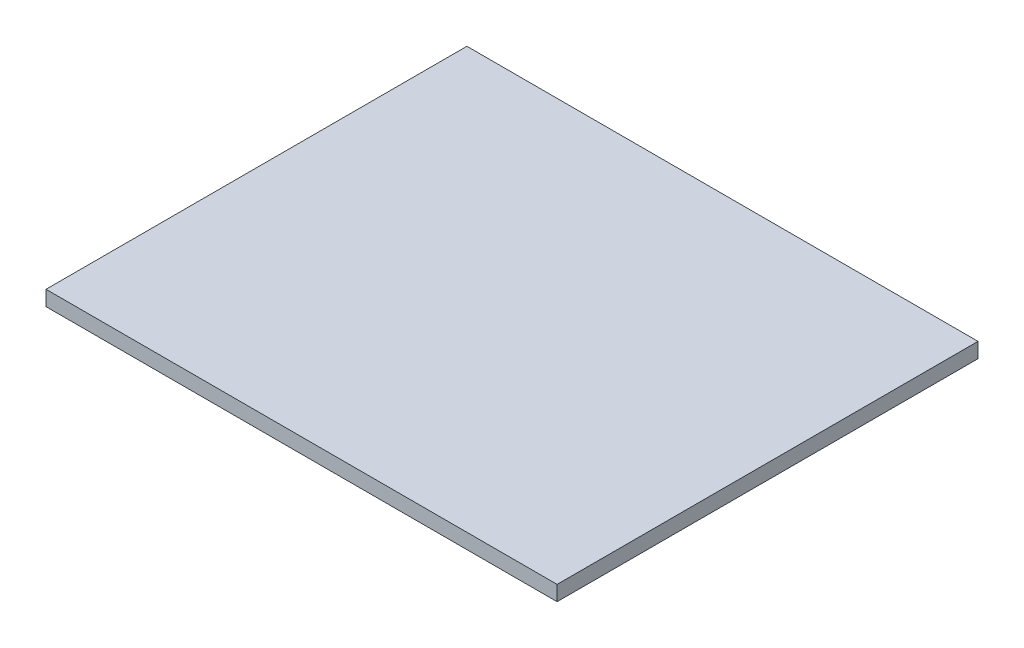
SolidWorks part; units mm, degrees
ref_plane "정면" through (0, 0, 0) normal (0, 0, 1) x (1, 0, 0)
ref_plane "윗면" through (0, 0, 0) normal (0, 1, 0) x (1, 0, 0)
ref_plane "우측면" through (0, 0, 0) normal (1, 0, 0) x (0, 0, -1)
sketch "스케치1" plane through (0, 0, 0) normal (0, 1, 0) x (1, 0, 0)
  line L1 (0, 0) -> (170, 0)
  line L2 (0, 0) -> (0, 140)
  line L3 (0, 140) -> (170, 140)
  line L4 (170, 0) -> (170, 140)
  dimension "D1" = 170
  dimension "D2" = 140
extrude "보스-돌출1" add sketch "스케치1" along normal blind 5
hole_wizard "M4 여유 구멍1" positions "스케치3" profile "스케치2" hole size "M4" standard "Ansi Metric"
sketch "스케치3" plane through (0, 5, 0) normal (0, 1, 0) x (1, 0, 0)
  line L0 (18.0385, 100) -> (121.9615, 100) construction
  line L1 (121.9615, 100) -> (70, 10) construction
  line L2 (70, 10) -> (18.0385, 100) construction
  line L4 (0, 0) -> (140, 0) construction
  line L5 (70, 100) -> (70, 110) construction
  line L6 (140, 110) -> (0, 110) construction
  point P0 (18.0385, 100)
  point P2 (121.9615, 100)
  point P4 (70, 10)
  dimension "D1" = 10
  dimension "D2" = 10
sketch "스케치2" plane through (18.0385, 5, -100) normal (1, 0, 0) x (0, 0, 1)
  line L0 (0, 0) -> (0, 21.3519)
  line L1 (0, 21.3519) -> (2.25, 20)
  line L2 (2.25, 20) -> (2.25, 0)
  line L5 (2.25, 0) -> (0, 0)
  line L10 (0, 21.3519) -> (-2.25, 20) construction
  line L11 (0, -6.35) -> (0, 107.95) construction
  dimension "구멍 지름" = 4.5
  dimension "구멍 깊이" = 20
  dimension "드릴 각도" = 118
